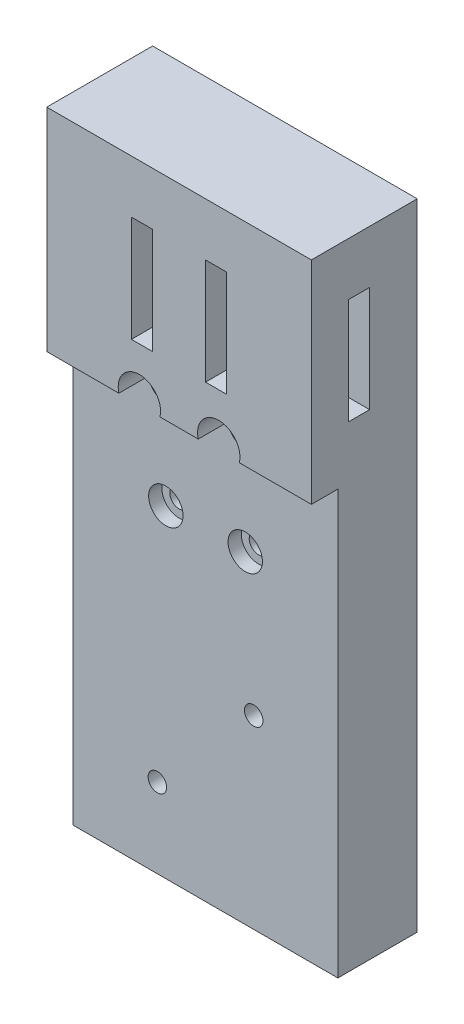
SolidWorks part; units mm, degrees
ref_plane "Front Plane" through (0, 0, 0) normal (0, 0, 1) x (1, 0, 0)
ref_plane "Top Plane" through (0, 0, 0) normal (0, 1, 0) x (1, 0, 0)
ref_plane "Right Plane" through (0, 0, 0) normal (1, 0, 0) x (0, 0, -1)
sketch "Sketch1" plane through (0, 0, 0) normal (0, 0, 1) x (1, 0, 0)
  line L1 (0, 0) -> (50, 0)
  line L2 (0, 0) -> (0, 100)
  line L3 (0, 100) -> (50, 100)
  line L4 (50, 0) -> (50, 100)
  dimension "D1" = 100
  dimension "D2" = 50
extrude "Boss-Extrude1" add sketch "Sketch1" along normal blind 20
sketch "Sketch2" plane through (0, 0, 0) normal (-1, 0, 0) x (0, 0, 1)
  line L0 (20, 100) -> (0, 100) construction
  line L1 (9, 90) -> (13, 90)
  line L2 (9, 90) -> (9, 70)
  line L3 (9, 70) -> (13, 70)
  line L4 (13, 90) -> (13, 70)
  line L9 (20, 100) -> (20, 0) construction
  dimension "D1" = 10
  dimension "D2" = 7
  dimension "D3" = 4
  dimension "D4" = 20
extrude "Cut-Extrude1" cut sketch "Sketch2" against normal blind 20
sketch "Sketch3" plane through (0, 0, 20) normal (0, 0, 1) x (1, 0, 0)
  line L0 (0, 100) -> (0, 0) construction
  line L1 (16, 90) -> (20, 90)
  line L2 (16, 90) -> (16, 70)
  line L3 (16, 70) -> (20, 70)
  line L4 (20, 90) -> (20, 70)
  line L5 (50, 100) -> (0, 100) construction
  dimension "D1" = 20
  dimension "D2" = 4
  dimension "D3" = 10
  dimension "D4" = 20
extrude "Cut-Extrude2" cut sketch "Sketch3" against normal blind 16
ref_plane "Plane1" through (25, 0, 0) normal (-1, 0, 0) x (0, 0, 1)
mirror "Mirror1" about plane through (25, 0, 0) normal (-1, 0, 0) of "Cut-Extrude2", "Cut-Extrude1"
sketch "Sketch4" plane through (0, 0, 0) normal (-1, 0, 0) x (0, 0, 1)
  line L0 (0, 100) -> (0, 0) construction
  line L2 (0, 50) -> (0, 0)
  line L3 (0, 0) -> (15, 0)
  line L5 (20, 0) -> (0, 0) construction
  line L6 (15, 0) -> (15, 60)
  line L7 (20, 100) -> (20, 0) construction
  line L8 (20, 0) -> (0, 0)
  line L9 (20, 100) -> (20, 0)
  line L10 (15, 60) -> (20, 60)
  line L12 (20, 100) -> (0, 100) construction
  dimension "D3" = 40
  dimension "D1" = 15
  dimension "D2" = 50
extrude "Cut-Extrude3" cut sketch "Sketch4" against normal through all
sketch "Sketch6" plane through (0, 0, 20) normal (0, 0, 1) x (1, 0, 0)
  line L4 (0, 60) -> (50, 60)
  line L5 (50, 60) -> (50, 100)
  line L6 (50, 100) -> (0, 100)
  line L7 (0, 100) -> (0, 60)
  line L8 (0, 60) -> (50, 60)
  line L9 (50, 60) -> (50, 100)
  line L10 (50, 100) -> (0, 100)
  line L11 (0, 100) -> (0, 60)
  circle A0 centre (32.5, 61) radius 1.625 construction
  circle A1 centre (32.5, 61) radius 1.625 construction
  circle A2 centre (17.5, 61) radius 1.625 construction
  circle A3 centre (32.5, 41) radius 1.625 construction
  circle A4 centre (17.5, 41) radius 1.625 construction
  circle A5 centre (17.5, 61) radius 1.625 construction
  circle A6 centre (32.5, 41) radius 1.625 construction
  circle A7 centre (17.5, 41) radius 1.625 construction
  circle A8 centre (32.5, 61) radius 1.75
  circle A9 centre (17.5, 61) radius 1.75
  circle A10 centre (17.5, 41) radius 1.75
  circle A11 centre (32.5, 41) radius 1.75
  dimension "D2" = 3.5
  dimension "D3" = 3.5
  dimension "D4" = 3.5
  dimension "D5" = 3.5
  dimension "D1" = 0
extrude "Cut-Extrude5" cut sketch "Sketch6" against normal through all contours L8 A9 | L8 A8 | L8 A8 | A11 | A10 | L8 A9
sketch "Sketch7" plane through (0, 0, 20) normal (0, 0, 1) x (1, 0, 0)
  circle A0 centre (32.5, 61) radius 4
  circle A1 centre (17.5, 61) radius 4
  dimension "D1" = 8
  dimension "D2" = 8
extrude "Cut-Extrude6" cut sketch "Sketch7" against normal up to surface (5 mm away) up to face at (25, 44.8125, 15)
sketch "Sketch8" plane through (0, 0, 15) normal (0, 0, 1) x (1, 0, 0)
  circle A0 centre (17.5, 61) radius 3.25
  circle A1 centre (32.5, 61) radius 3.25
  circle A2 centre (32.5, 41) radius 3.25
  circle A3 centre (17.5, 41) radius 1.75 construction
  circle A4 centre (17.5, 41) radius 1.75 construction
  circle A5 centre (17.5, 41) radius 3.25
  dimension "D1" = 6.5
  dimension "D2" = 6.5
  dimension "D3" = 6.5
  dimension "D4" = 6.5
extrude "Cut-Extrude7" cut sketch "Sketch8" against normal blind 2.5
sketch "Sketch9" plane through (0, 0, 15) normal (0, 0, 1) x (1, 0, 0)
  line L0 (50, 0) -> (50, 60) construction
  line L1 (0, 0) -> (50, 0)
  line L2 (0, 0) -> (0, -20)
  line L3 (0, -20) -> (50, -20)
  line L4 (50, 0) -> (50, -20)
  dimension "D1" = 20
extrude "Boss-Extrude2" add sketch "Sketch9" against normal up to surface (15 mm away) up to face at (19.25, 61, 0)
sketch "Sketch5" plane through (0, 0, 15) normal (0, 0, 1) x (1, 0, 0)
  line L0 (0, 20) -> (50, 20) construction
  line L1 (25, 20) -> (25, -15.2448) construction
  line L2 (25, 11) -> (25, -11) construction
  line L3 (15.9, -5) -> (34.1, -5)
  line L4 (34.1, 15) -> (34.1, -5)
  line L6 (50, 60) -> (36.373, 60) construction
  circle A0 centre (34.1, 15) radius 1.75
  circle A1 centre (15.9, -5) radius 1.75
  point P12 (25, -5)
  point P14 (0, 0)
  point P15 (0, 0)
  point P16 (0, 0)
  point P17 (0, 0)
  point P18 (0, 0)
  dimension "D4" = 3.5
  dimension "D5" = 3.5
  dimension "D1" = 5
  dimension "D2" = 20
  dimension "D3" = 18.2
  dimension "D6" = 40
extrude "Cut-Extrude4" cut sketch "Sketch5" against normal through all
